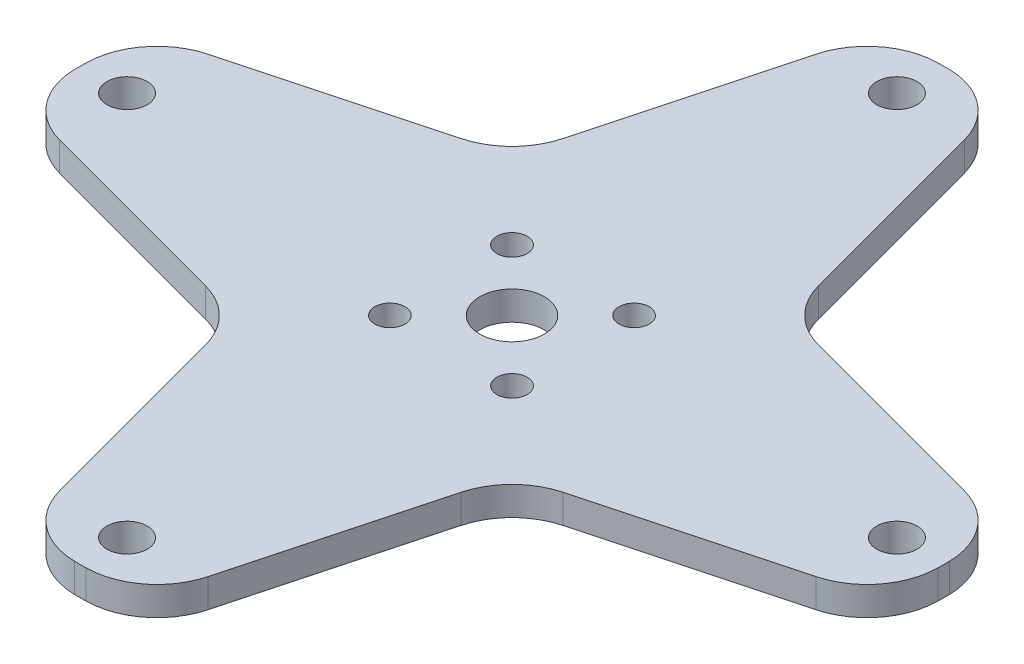
SolidWorks part; units mm, degrees
ref_plane "前视基准面" through (0, 0, 0) normal (0, 0, 1) x (1, 0, 0)
ref_plane "上视基准面" through (0, 0, 0) normal (0, 1, 0) x (1, 0, 0)
ref_plane "右视基准面" through (0, 0, 0) normal (1, 0, 0) x (0, 0, -1)
other "Configuration Table"
sketch "草图1" plane through (0, 0, 0) normal (0, 1, 0) x (1, 0, 0)
  line L0 (0, 0) -> (0, 60) construction
  line L1 (0, 0) -> (60, 0) construction
  line L2 (0, 0) -> (42.4264, 42.4264) construction
  line L3 (0, 0) -> (42.4264, -42.4264) construction
  line L4 (8.4853, 59.397) -> (24.4007, 0)
  line L5 (8.4853, 59.397) -> (8.4853, 0) construction
  line L6 (-8.4853, 59.397) -> (-24.4007, 0)
  line L7 (8.4853, -59.397) -> (24.4007, 0)
  line L8 (-8.4853, -59.397) -> (-24.4007, 0)
  line L9 (59.397, -8.4853) -> (0, -24.4007)
  line L10 (-59.397, -8.4853) -> (0, -24.4007)
  line L11 (59.397, 8.4853) -> (0, 24.4007)
  line L12 (-59.397, 8.4853) -> (0, 24.4007)
  circle A0 centre (0, 0) radius 60
  circle A1 centre (0, 53.5) radius 2.8
  circle A2 centre (53.5, 0) radius 2.8
  circle A3 centre (0, -53.5) radius 2.8
  circle A4 centre (-53.5, 0) radius 2.8
  circle A11 centre (0, 0) radius 4.5
  circle A12 centre (8.4853, 8.4853) radius 2.1
  circle A13 centre (8.4853, -8.4853) radius 2.1
  circle A14 centre (-8.4853, -8.4853) radius 2.1
  circle A15 centre (-8.4853, 8.4853) radius 2.1
  dimension "D1" = 120
  dimension "D4" = 5.6
  dimension "D5" = 9
  dimension "D6" = 12
  dimension "D8" = 4.2
  dimension "D9" = 75
  dimension "D2" = 45
  dimension "D3" = 53.5
  dimension "D7" = 45
extrude "凸台-拉伸1" add sketch "草图1" along normal blind 4 contours L12 A0 L10 L8 L6 A4 | L12 L6 L8 L10 L9 L7 L4 L11 A13 A12 A11 A14 A15 | L4 A0 L6 L12 L11 A1 | L9 A0 L11 L4 L7 A2 | L8 A0 L7 L9 L10 A3
fillet "圆角1" radius 10 12 edges at (-19.2442, 2, 19.2442) (-8.4853, 2, 59.397) (8.4853, 2, 59.397) (19.2442, 2, 19.2442) (59.397, 2, 8.4853) (59.397, 2, -8.4853) (19.2442, 2, -19.2442) (8.4853, 2, -59.397) (-8.4853, 2, -59.397) (-19.2442, 2, -19.2442) (-59.397, 2, 8.4853) (-59.397, 2, -8.4853)
